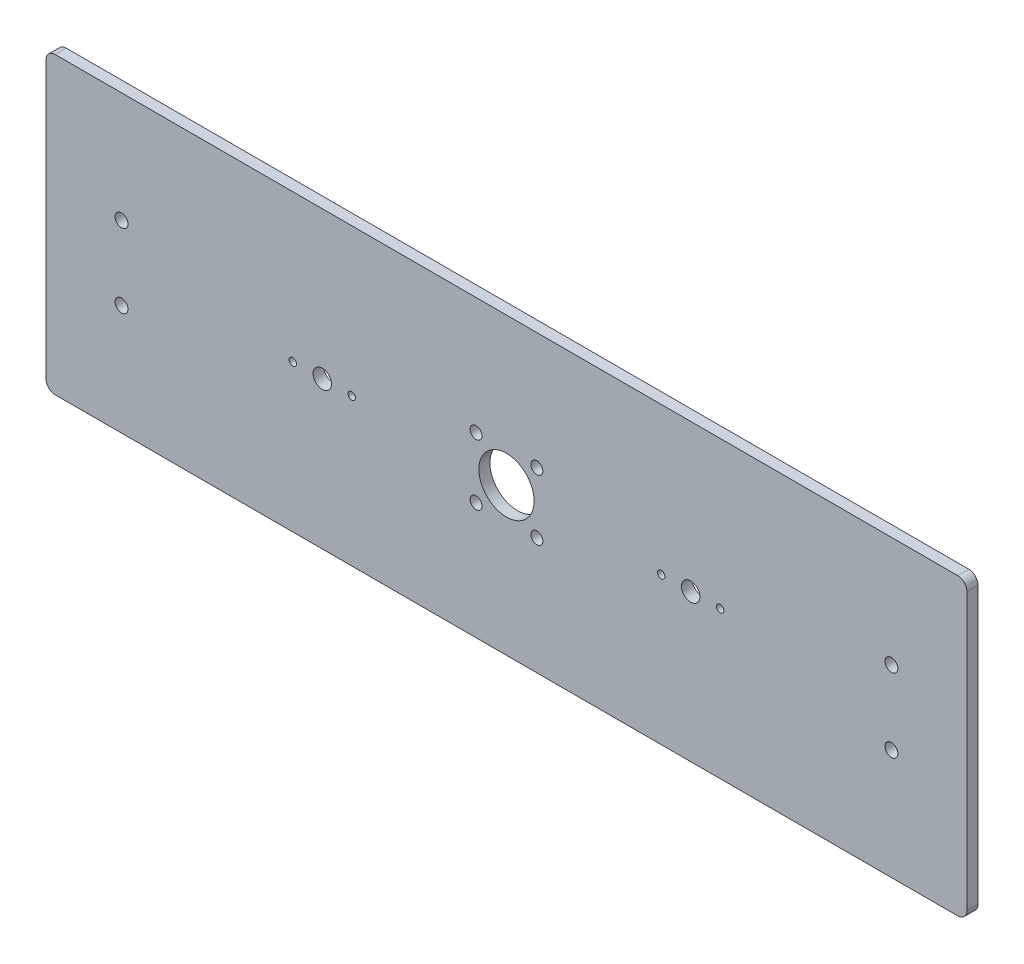
SolidWorks part; units mm, degrees
ref_plane "Front Plane" through (0, 0, 0) normal (0, 0, 1) x (1, 0, 0)
ref_plane "Top Plane" through (0, 0, 0) normal (0, 1, 0) x (1, 0, 0)
ref_plane "Right Plane" through (0, 0, 0) normal (1, 0, 0) x (0, 0, -1)
sketch "Sketch2" plane through (0, 0, 0) normal (0, 0, 1) x (1, 0, 0)
  line L0 (-175.842, 0) -> (185.0644, 0) construction
  line L1 (-200, -80) -> (300, -80)
  line L2 (-200, -80) -> (-200, 80)
  line L3 (-200, 80) -> (300, 80)
  line L4 (300, -80) -> (300, 80)
  line L5 (-177.1639, -15) -> (183.7426, -15) construction
  line L6 (-177.1639, 15) -> (183.7426, 15) construction
  line L7 (50, 80) -> (50, -80) construction
  line L8 (150, 5) -> (150, -5) construction
  line L9 (134, 5) -> (134, -5) construction
  line L10 (166, 5) -> (166, -5) construction
  circle A18 centre (50, 0) radius 15
  circle A19 centre (-50, 0) radius 5
  circle A20 centre (150, 0) radius 5
  circle A21 centre (-159, 20) radius 3.5
  circle A25 centre (-159, -20) radius 3.5
  circle A26 centre (259, -20) radius 3.5
  circle A27 centre (259, 20) radius 3.5
  circle A28 centre (134, 0) radius 2
  circle A29 centre (166, 0) radius 2
  circle A30 centre (-66, 0) radius 2
  circle A31 centre (-34, 0) radius 2
  circle A32 centre (50, 0) radius 23.3345 construction
  circle A33 centre (66.5, 16.5) radius 3.25
  circle A34 centre (33.5, 16.5) radius 3.25
  circle A35 centre (33.5, -16.5) radius 3.25
  circle A36 centre (66.5, -16.5) radius 3.25
  dimension "D2" = 100
  dimension "D4" = 30
  dimension "D5" = 10
  dimension "D6" = 500
  dimension "D7" = 209
  dimension "D8" = 209
  dimension "D9" = 209
  dimension "D10" = 209
  dimension "D11" = 250
  dimension "D12" = 100
  dimension "D13" = 160
  dimension "D3" = 10
  dimension "D14" = 20
  dimension "D15" = 20
  dimension "D16" = 20
  dimension "D17" = 20
  dimension "D18" = 7
  dimension "D19" = 7
  dimension "D20" = 7
  dimension "D21" = 7
  dimension "D24" = 16
  dimension "D25" = 16
extrude "Boss-Extrude1" add sketch "Sketch2" along normal blind 6
fillet "Fillet1" radius 5 4 edges at (-200, -80, 3) (300, -80, 3) (300, 80, 3) (-200, 80, 3)
